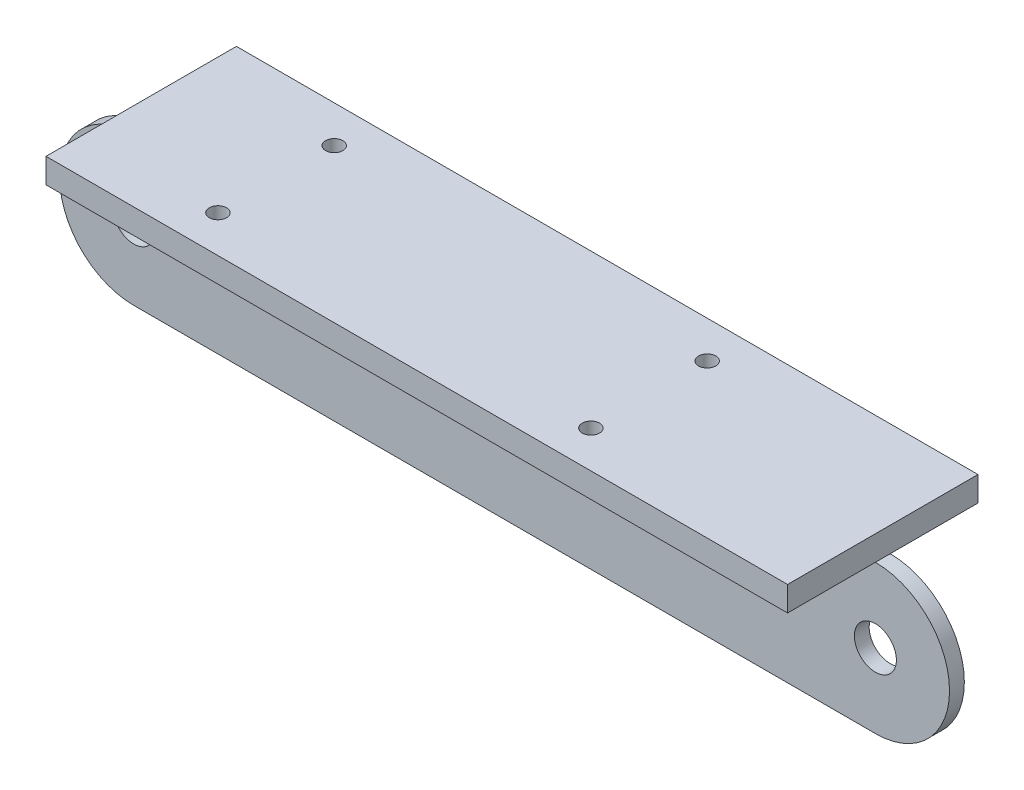
SolidWorks part; units mm, degrees
ref_plane "Plano frontal" through (0, 0, 0) normal (0, 0, 1) x (1, 0, 0)
ref_plane "Plano superior" through (0, 0, 0) normal (0, 1, 0) x (1, 0, 0)
ref_plane "Plano direito" through (0, 0, 0) normal (1, 0, 0) x (0, 0, -1)
sketch "Esboço1" plane through (0, 0, 0) normal (0, 0, 1) x (1, 0, 0)
  line L0 (64.7929, 11.1834) -> (-85.2071, 11.1834) construction
  line L1 (-85.2071, 26.1834) -> (64.7929, 26.1834)
  line L3 (-85.2071, -3.8166) -> (64.7929, -3.8166)
  arc A0 (64.7929, 26.1834) -> (64.7929, -3.8166) centre (64.7929, 11.1834) cw
  arc A1 (-85.2071, -3.8166) -> (-85.2071, 26.1834) centre (-85.2071, 11.1834) cw
  circle A3 centre (-85.2071, 11.1834) radius 4.25
  circle A4 centre (64.7929, 11.1834) radius 4.25
  dimension "D3" = 8.5
  dimension "D4" = 8.5
  dimension "D1" = 150
  dimension "D2" = 30
extrude "Ressalto-extrusão1" add sketch "Esboço1" along normal blind 3
sketch "Esboço2" plane through (0, 26.1834, 0) normal (0, 1, 0) x (1, 0, 0)
  line L0 (64.7929, -3) -> (64.7929, 0) construction
  line L1 (-85.2071, 17.76) -> (64.7929, 17.76)
  line L2 (-85.2071, 17.76) -> (-85.2071, -20.76)
  line L3 (-85.2071, -20.76) -> (64.7929, -20.76)
  line L4 (64.7929, 17.76) -> (64.7929, -20.76)
  dimension "D1" = 0
  dimension "D2" = 38.52
  dimension "D3" = 17.76
  dimension "D4" = 17.76
extrude "Ressalto-extrusão2" add sketch "Esboço2" along normal blind 5
sketch "Esboço3" plane through (-85.2071, 0, 0) normal (-1, 0, 0) x (0, 0, 1)
  line L0 (3, 19.6834) -> (9.5, 26.1834)
  line L1 (3, -3.8166) -> (3, 26.1834) construction
  line L2 (3, 26.1834) -> (20.76, 26.1834) construction
  line L3 (9.5, 26.1834) -> (3, 26.1834)
  line L4 (3, 26.1834) -> (3, 19.6834)
  line L5 (0, 26.1834) -> (0, 19.6834)
  line L6 (0, 26.1834) -> (0, -3.8166) construction
  line L7 (0, 19.6834) -> (-6.5, 26.1834)
  line L8 (-17.76, 26.1834) -> (0, 26.1834) construction
  line L9 (-6.5, 26.1834) -> (0, 26.1834)
  dimension "D1" = 6.5
  dimension "D2" = 6.5
  dimension "D3" = 6.5
extrude "Ressalto-extrusão3" add sketch "Esboço3" against normal blind 100 from offset 25 offset against normal yes
sketch "Esboço4" plane through (0, 31.1834, 0) normal (0, 1, 0) x (1, 0, 0)
  line L0 (64.7929, -20.76) -> (64.7929, 17.76) construction
  line L2 (-85.2071, 17.76) -> (-85.2071, -20.76) construction
  line L4 (64.7929, -1.5) -> (-85.2071, -1.5) construction
  line L5 (-85.2071, -20.76) -> (64.7929, -20.76) construction
  line L6 (-85.2071, -3) -> (-85.2071, 0) construction
  circle A0 centre (17.5129, 10.26) radius 1.75
  circle A1 centre (17.5129, -13.26) radius 1.75
  circle A2 centre (-57.9271, -13.26) radius 1.75
  circle A3 centre (-57.9271, 10.26) radius 1.75
  dimension "D1" = 7.5
  dimension "D2" = 47.28
  dimension "D3" = 27.28
  dimension "D4" = 27.28
  dimension "D5" = 75.44
  dimension "D6" = 7.5
extrude "Corte-extrusão1" cut sketch "Esboço4" against normal blind 10
